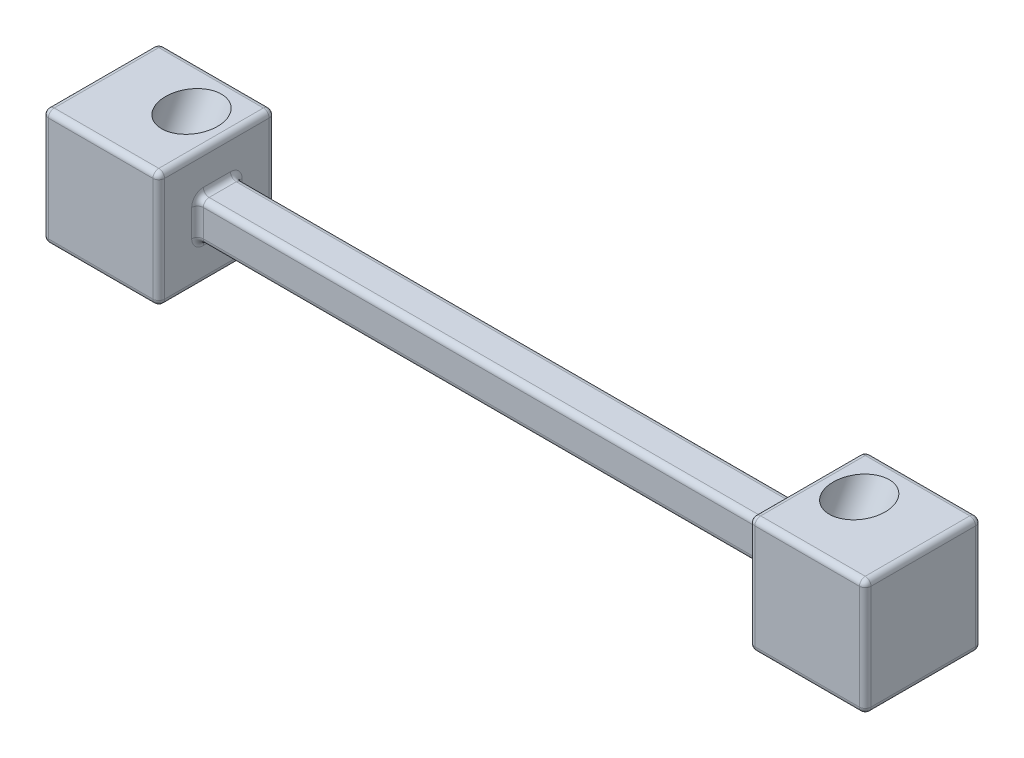
SolidWorks part; units mm, degrees
ref_plane "Front Plane" through (0, 0, 0) normal (0, 0, 1) x (1, 0, 0)
ref_plane "Top Plane" through (0, 0, 0) normal (0, 1, 0) x (1, 0, 0)
ref_plane "Right Plane" through (0, 0, 0) normal (1, 0, 0) x (0, 0, -1)
sketch "Sketch1" plane through (0, 0, 0) normal (1, 0, 0) x (0, 0, -1)
  line L0 (-17.3205, 0) -> (12.6795, 0)
  line L1 (12.6795, 30) -> (-17.3205, 30)
  line L2 (-17.3205, 30) -> (-17.3205, 0)
  line L3 (12.6795, 30) -> (12.6795, 0)
  dimension "D1" = 30
  dimension "D2" = 30
extrude "Boss-Extrude1" add sketch "Sketch1" along normal blind 30 contours L2 L0 L3 L1
sketch "Sketch2" plane through (30, 0, 0) normal (1, 0, 0) x (0, 0, -1)
  line L0 (2.6795, 0) -> (2.6795, 10) construction
  line L1 (-7.3205, 20) -> (2.6795, 20)
  line L2 (-7.3205, 20) -> (-7.3205, 10)
  line L3 (-7.3205, 10) -> (2.6795, 10)
  line L4 (2.6795, 20) -> (2.6795, 10)
  line L5 (-17.3205, 0) -> (12.6795, 0) construction
  line L6 (12.6795, 10) -> (2.6795, 10) construction
  line L7 (12.6795, 30) -> (12.6795, 0) construction
  line L8 (-7.3205, 30) -> (-7.3205, 20) construction
  line L9 (12.6795, 30) -> (-17.3205, 30) construction
  line L10 (-7.3205, 20) -> (-17.3205, 20) construction
  line L11 (-17.3205, 30) -> (-17.3205, 0) construction
  dimension "D1" = 10
extrude "Boss-Extrude2" add sketch "Sketch2" along normal blind 152.4
sketch "Sketch3" plane through (182.4, 0, 0) normal (1, 0, 0) x (0, 0, -1)
  line L0 (0.6795, 10) -> (0.6795, 12) construction
  line L1 (-5.3205, 18) -> (0.6795, 18)
  line L2 (-5.3205, 18) -> (-5.3205, 12)
  line L3 (-5.3205, 12) -> (0.6795, 12)
  line L4 (0.6795, 18) -> (0.6795, 12)
  line L5 (-7.3205, 10) -> (2.6795, 10) construction
  line L6 (0.6795, 12) -> (2.6795, 12) construction
  line L7 (2.6795, 10) -> (2.6795, 20) construction
  line L9 (2.6795, 20) -> (-7.3205, 20) construction
  line L10 (-5.3205, 20) -> (-5.3205, 18) construction
  line L11 (-5.3205, 18) -> (-7.3205, 18) construction
  line L12 (-7.3205, 20) -> (-7.3205, 10) construction
  dimension "D1" = 6
extrude "Cut-Extrude1" cut sketch "Sketch3" against normal up to surface (152.4 mm away) up to face at (30, 15, 2.3205)
sketch "Sketch4" plane through (0, 30, 0) normal (0, 1, 0) x (1, 0, 0)
  line L0 (20, 12.6795) -> (20, 2.6795) construction
  line L1 (30, 12.6795) -> (0, 12.6795) construction
  line L2 (20, 2.6795) -> (30, 2.6795) construction
  line L3 (30, 12.6795) -> (30, -17.3205) construction
  circle A0 centre (20, 2.6795) radius 6.2
  dimension "D1" = 10
  dimension "D3" = 12.4
  dimension "D2" = 10
sketch "Sketch5" plane through (0, 0, 0) normal (-1, 0, 0) x (0, 0, 1)
  line L0 (-2.6795, 30) -> (7.3205, 12.6795)
  line L1 (3.5205, 30) -> (-8.8795, 30) construction
  line L2 (-12.6795, 30) -> (17.3205, 30) construction
  dimension "D1" = 60
  dimension "D2" = 20
sweep "Cut-Sweep1" [suppressed] cut profiles "Sketch4" path "Sketch5"
sketch "Sketch6" plane through (0, 0, -12.6795) normal (0, 0, -1) x (-1, 0, 0)
  line L0 (0, 15) -> (-10, 15) construction
  line L1 (0, 30) -> (0, 0) construction
  circle A0 centre (-10, 15) radius 4.5
  dimension "D1" = 9
extrude "Cut-Extrude2" cut sketch "Sketch6" against normal blind 15
ref_plane "Plane1" through (106.2, 0, 0) normal (1, 0, 0) x (0, 0, -1)
ref_plane "Plane2" through (0, 27.9904, -16.1603) normal (0, 0.866, -0.5) x (-1, 0, 0)
sketch "Sketch7" plane through (0, 27.9904, -16.1603) normal (0, 0.866, -0.5) x (-1, 0, 0)
  line L0 (-30, 4.0192) -> (-20, 4.0192) construction
  line L1 (-30, 4.0192) -> (0, 4.0192) construction
  line L2 (-20, 4.0192) -> (-20, 14.0192) construction
  circle A0 centre (-20, 14.0192) radius 6.7
  dimension "D1" = 13.4
  dimension "D2" = 10
  dimension "D3" = 10
extrude "Cut-Extrude3" cut sketch "Sketch7" against normal blind 20
mirror "Mirror1" about plane through (106.2, 0, 0) normal (1, 0, 0) of "Cut-Extrude3", "Cut-Extrude2", "Boss-Extrude1"
fillet "Fillet1" radius 1.5 37 edges at (15, 0, -12.6795) (15, 30, 17.3205) (15, 0, 17.3205) (0, 15, 17.3205) (0, 0, 2.3205) (0, 15, -12.6795) (0, 30, 2.3205) (30, 15, -12.6795) (30, 0, 2.3205) (30, 15, 17.3205) (30, 30, 2.3205) (212.4, 15, -12.6795) (212.4, 30, 2.3205) (197.4, 30, 17.3205) (212.4, 15, 17.3205) (182.4, 15, 17.3205) (182.4, 15, -12.6795) (182.4, 30, 2.3205) (197.4, 0, -12.6795) (182.4, 0, 2.3205) (197.4, 0, 17.3205) (212.4, 0, 2.3205) (182.4, 15, 7.3205) (30, 15, 7.3205) (106.2, 10, 7.3205) (182.4, 10, 2.3205) (30, 10, 2.3205) (106.2, 10, -2.6795) (182.4, 15, -2.6795) (30, 15, -2.6795) (106.2, 20, -2.6795) (182.4, 20, 2.3205) (106.2, 20, 7.3205) (30, 20, 2.3205) (15, 30, -12.6795) (197.4, 30, -12.6795) (106.2, 12, -0.6795)
